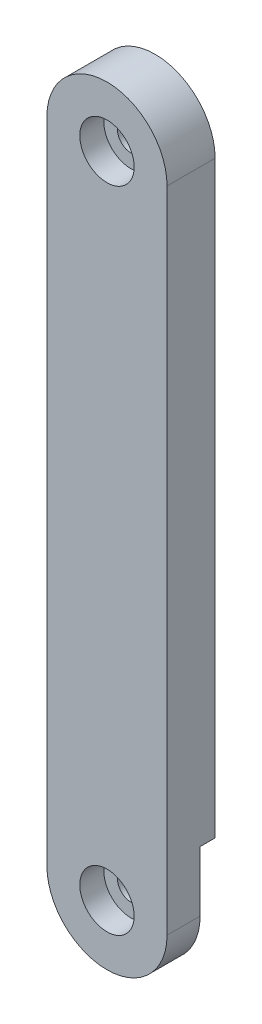
SolidWorks part; units mm, degrees
ref_plane "Front Plane" through (0, 0, 0) normal (0, 0, 1) x (1, 0, 0)
ref_plane "Top Plane" through (0, 0, 0) normal (0, 1, 0) x (1, 0, 0)
ref_plane "Right Plane" through (0, 0, 0) normal (1, 0, 0) x (0, 0, -1)
sketch "Sketch1" plane through (0, 0, 0) normal (0, 0, 1) x (1, 0, 0)
  line L0 (10, 0) -> (10, 108)
  line L1 (-10, 108) -> (-10, 0)
  arc A0 (10, 108) -> (-10, 108) centre (0, 108) ccw
  arc A1 (-10, 0) -> (10, 0) centre (0, 0) ccw
  circle A2 centre (0, 0) radius 2.25
  circle A3 centre (0, 108) radius 2.25
extrude "Boss-Extrude1" add sketch "Sketch1" along normal blind 8
sketch "Sketch2" plane through (0, 0, 8) normal (0, 0, 1) x (1, 0, 0)
  circle A0 centre (0, 0) radius 4.525
  circle A1 centre (0, 108) radius 4.525
extrude "Cut-Extrude1" cut sketch "Sketch2" against normal blind 4
sketch "Sketch3" plane through (0, 0, 0) normal (0, 0, 1) x (1, 0, 0)
  line L0 (7.5, 12) -> (7.5, 96)
  line L1 (-7.5, 96) -> (-7.5, 12)
  arc A0 (7.5, 96) -> (-7.5, 96) centre (0, 108) cw
  arc A1 (-7.5, 12) -> (7.5, 12) centre (0, 0) ccw
extrude "Cut-Extrude2" cut sketch "Sketch3" along normal blind 2.5
